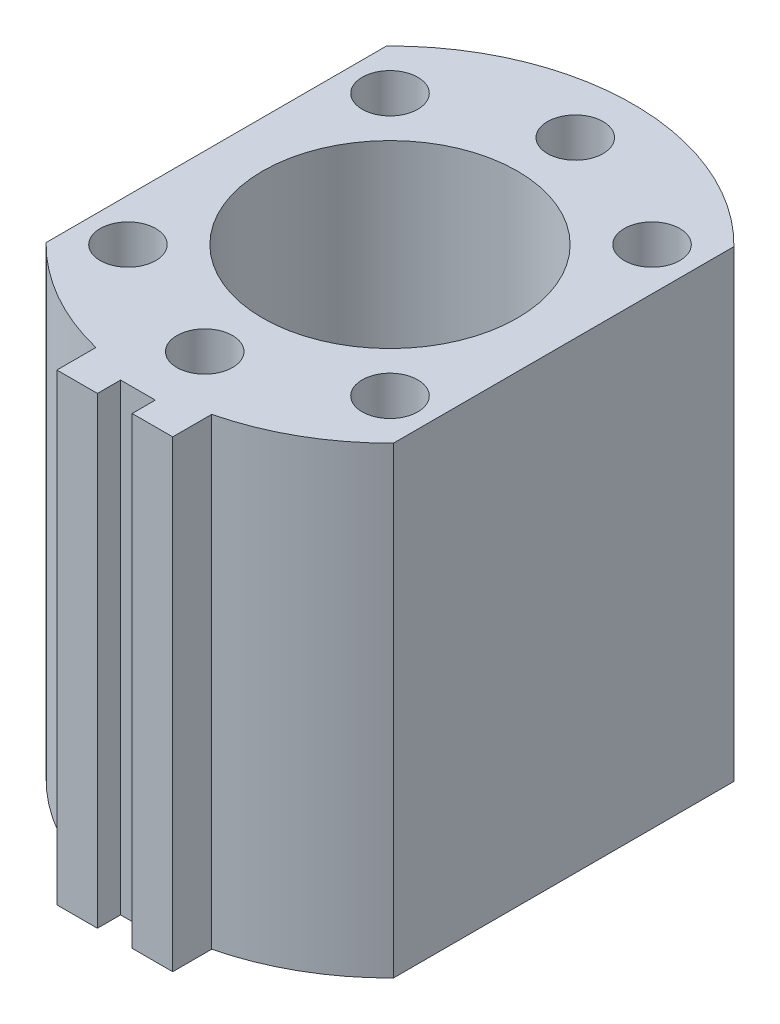
SolidWorks part; units mm, degrees
material "1060 合金"
ref_plane "前视基准面" through (0, 0, 0) normal (0, 0, 1) x (1, 0, 0)
ref_plane "上视基准面" through (0, 0, 0) normal (0, 1, 0) x (1, 0, 0)
ref_plane "右视基准面" through (0, 0, 0) normal (1, 0, 0) x (0, 0, -1)
sketch "草图1" plane through (0, 0, 0) normal (0, 1, 0) x (1, 0, 0)
  line L0 (-15, 14.6969) -> (-15, -14.6969)
  line L1 (15, 14.6969) -> (15, -14.6969)
  arc A0 (-15, -14.6969) -> (15, -14.6969) centre (0, 0) ccw
  arc A1 (15, 14.6969) -> (-15, 14.6969) centre (0, 0) ccw
  dimension "D1" = 15
  dimension "D3" = 42
  dimension "D2" = 15
extrude "凸台-拉伸1" add sketch "草图1" along normal blind 40
sketch "草图2" plane through (0, 40, 0) normal (0, 1, 0) x (1, 0, 0)
  circle A0 centre (0, 0) radius 11
  dimension "D1" = 22
extrude "切除-拉伸1" cut sketch "草图2" against normal through all
sketch "草图3" plane through (0, 40, 0) normal (0, 1, 0) x (1, 0, 0)
  circle A1 centre (-11.3137, 11.3137) radius 2.4
  dimension "D1" = 4.8
  dimension "D2" = 16
extrude "切除-拉伸2" cut sketch "草图3" against normal blind 8
pattern_circular "阵列(圆周)2" count 8 over 360 about axis through (0, 40, 0) along (0, 1, 0) skipping 1, 5 of "切除-拉伸2"
sketch "草图4" plane through (0, 0, 0) normal (0, 1, 0) x (1, 0, 0)
  line L1 (-5, -20.3961) -> (5, -20.3961)
  line L2 (-5, -20.3961) -> (-5, -23.764)
  line L3 (-5, -23.764) -> (5, -23.764)
  line L4 (5, -20.3961) -> (5, -23.764)
  arc A0 (-15, -14.6969) -> (15, -14.6969) centre (0, 0) ccw construction
  dimension "D1" = 5
  dimension "D2" = 5
extrude "凸台-拉伸2" add sketch "草图4" along normal blind 40
sketch "草图5" plane through (0, 0, 0) normal (0, 1, 0) x (1, 0, 0)
  line L0 (-5, -23.764) -> (5, -23.764) construction
  line L1 (-1.5, -21.764) -> (1.5, -21.764)
  line L2 (-1.5, -21.764) -> (-1.5, -23.764)
  line L3 (-1.5, -23.764) -> (1.5, -23.764)
  line L4 (1.5, -21.764) -> (1.5, -23.764)
  dimension "D1" = 1.5
  dimension "D2" = 1.5
  dimension "D3" = 2
extrude "切除-拉伸3" cut sketch "草图5" along normal through all
